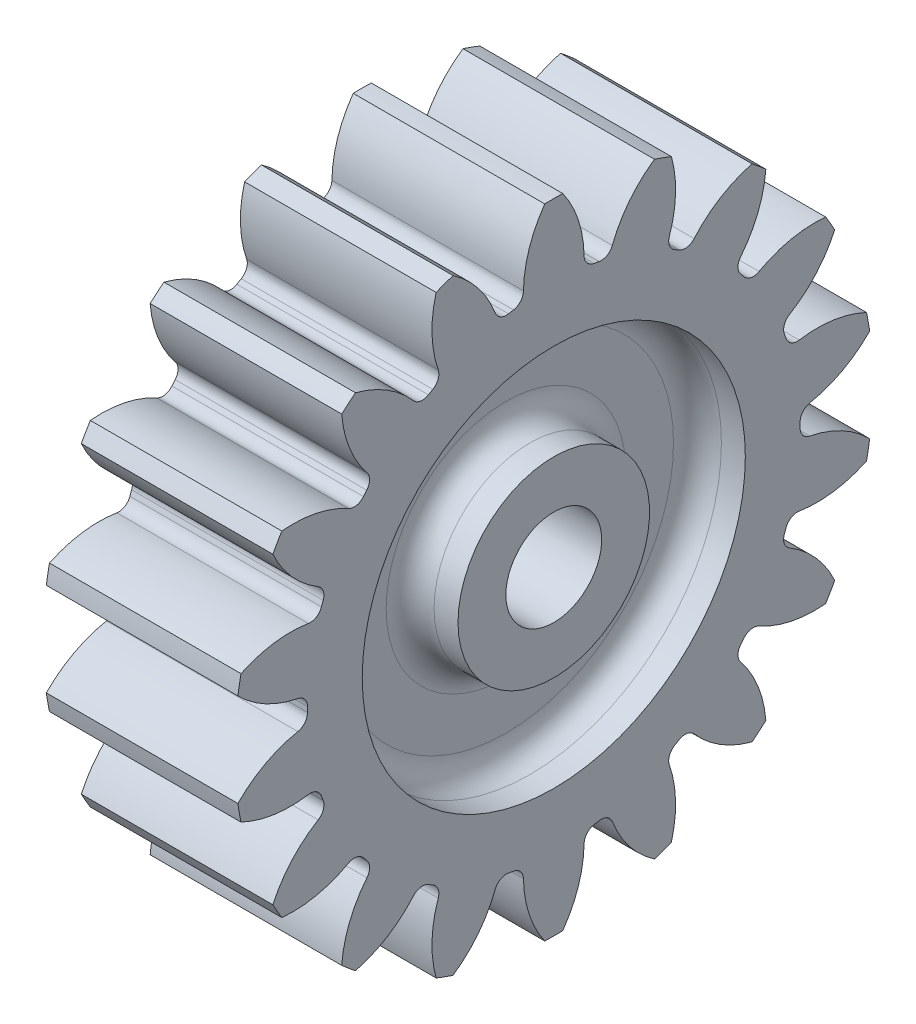
SolidWorks part; units mm, degrees
ref_plane "Front Plane" through (0, 0, 0) normal (0, 0, 1) x (1, 0, 0)
ref_plane "Top Plane" through (0, 0, 0) normal (0, 1, 0) x (1, 0, 0)
ref_plane "Right Plane" through (0, 0, 0) normal (1, 0, 0) x (0, 0, -1)
sketch "Sketch2" plane through (0, 0, 0) normal (0, 1, 0) x (1, 0, 0)
  line L0 (0, 2.4022) -> (0, -2.1136) construction
  line L1 (-2.9285, 0) -> (2.6948, 0) construction
  line L2 (-0.5, 0) -> (-0.5, 0.5)
  line L3 (-0.5, 1.667) -> (0.5, 1.667)
  line L4 (-0.5, 1) -> (-0.375, 1)
  line L5 (-0.25, 0.875) -> (-0.25, 0.625)
  line L6 (-0.375, 0.5) -> (-0.5, 0.5)
  line L7 (-0.5, 1) -> (-0.5, 1.667)
  line L8 (-0.5, 0.25) -> (0.5, 0.25)
  line L9 (0.5, 0) -> (0.5, 0.5)
  line L10 (0.375, 0.5) -> (0.5, 0.5)
  line L11 (0.25, 0.875) -> (0.25, 0.625)
  line L12 (0.5, 1) -> (0.375, 1)
  line L13 (0.5, 1) -> (0.5, 1.667)
  arc A0 (-0.25, 0.875) -> (-0.375, 1) centre (-0.375, 0.875) ccw
  arc A1 (-0.375, 0.5) -> (-0.25, 0.625) centre (-0.375, 0.625) ccw
  arc A2 (0.375, 0.5) -> (0.25, 0.625) centre (0.375, 0.625) cw
  arc A3 (0.25, 0.875) -> (0.375, 1) centre (0.375, 0.875) cw
  point P19 (0, 0.25)
  point P29 (0, 1.667)
  dimension "D6" = 0.125
  dimension "D7" = 0.125
  dimension "D1" = 1.667
  dimension "D2" = 0.5
  dimension "D3" = 0.5
  dimension "D4" = 1
  dimension "D5" = 0.25
  dimension "D8" = 0.25
revolve "Revolve1" add sketch "Sketch2" angle 360 about L1
sketch "Sketch3" plane through (0.5, 0, 0) normal (1, 0, 0) x (0, 0, -1)
  line L0 (0, 2.2686) -> (0, -2.043) construction
  line L1 (-2.6225, 0) -> (2.1229, 0) construction
  circle A0 centre (0, 0) radius 1.667
  circle A1 centre (0, 0) radius 1.286
  circle A2 centre (0, 0) radius 1.5
  arc A3 (-0.047, 1.6663) -> (-0.1584, 1.3287) centre (0.4415, 1.318) ccw
  arc A4 (0.047, 1.6663) -> (0.1585, 1.318) centre (-0.4415, 1.318) cw
  arc A5 (-0.2103, 1.2687) -> (-0.1584, 1.3287) centre (-0.2204, 1.3299) ccw
  arc A6 (0.2103, 1.2687) -> (0.1584, 1.3287) centre (0.2204, 1.3299) cw
  arc A7 (0.2363, 1.2641) -> (0.3056, 1.3028) centre (0.2477, 1.325) ccw
  arc A8 (0.5258, 1.5819) -> (0.3056, 1.3028) centre (0.8656, 1.0875) ccw
  arc A9 (0.6141, 1.5498) -> (0.5997, 1.1843) centre (0.0359, 1.3895) cw
  arc A10 (0.6315, 1.1203) -> (0.6033, 1.1944) centre (0.6619, 1.1743) cw
  arc A11 (0.6544, 1.107) -> (0.7328, 1.1197) centre (0.686, 1.1604) ccw
  arc A12 (1.0351, 1.3067) -> (0.7328, 1.1197) centre (1.1854, 0.7258) ccw
  arc A13 (1.1071, 1.2463) -> (0.9686, 0.9077) centre (0.509, 1.2934) cw
  arc A14 (0.9766, 0.8367) -> (0.9754, 0.9161) centre (1.0236, 0.8771) cw
  arc A15 (0.9936, 0.8164) -> (1.0715, 0.8016) centre (1.0415, 0.8558) ccw
  arc A16 (1.4196, 0.8739) -> (1.0715, 0.8016) centre (1.3621, 0.2766) ccw
  arc A17 (1.4666, 0.7925) -> (1.2206, 0.5217) centre (0.9206, 1.0413) cw
  arc A18 (1.2039, 0.4523) -> (1.2299, 0.5272) centre (1.2619, 0.4741) cw
  arc A19 (1.2129, 0.4274) -> (1.2811, 0.3867) centre (1.2714, 0.448) ccw
  arc A20 (1.6329, 0.3356) -> (1.2811, 0.3867) centre (1.3746, -0.2059) ccw
  arc A21 (1.6492, 0.2431) -> (1.3255, 0.0728) centre (1.2213, 0.6637) cw
  arc A22 (1.2859, 0.0132) -> (1.3361, 0.0747) centre (1.3479, 0.0139) cw
  arc A23 (1.2859, -0.0132) -> (1.3361, -0.0747) centre (1.3479, -0.0139) ccw
  arc A24 (1.6492, -0.2431) -> (1.3361, -0.0747) centre (1.2213, -0.6637) ccw
  arc A25 (1.6329, -0.3356) -> (1.2704, -0.385) centre (1.3746, 0.2059) cw
  arc A26 (1.2129, -0.4274) -> (1.2811, -0.3867) centre (1.2714, -0.448) cw
  arc A27 (1.2039, -0.4523) -> (1.2299, -0.5272) centre (1.2619, -0.4741) ccw
  arc A28 (1.4666, -0.7925) -> (1.2299, -0.5272) centre (0.9206, -1.0413) ccw
  arc A29 (1.4196, -0.8739) -> (1.0621, -0.7962) centre (1.3621, -0.2766) cw
  arc A30 (0.9936, -0.8164) -> (1.0715, -0.8016) centre (1.0415, -0.8558) cw
  arc A31 (0.9766, -0.8367) -> (0.9754, -0.9161) centre (1.0236, -0.8771) ccw
  arc A32 (1.1071, -1.2463) -> (0.9754, -0.9161) centre (0.509, -1.2934) ccw
  arc A33 (1.0351, -1.3067) -> (0.7257, -1.1115) centre (1.1854, -0.7258) cw
  arc A34 (0.6544, -1.107) -> (0.7328, -1.1197) centre (0.686, -1.1604) cw
  arc A35 (0.6315, -1.1203) -> (0.6033, -1.1944) centre (0.6619, -1.1743) ccw
  arc A36 (0.6141, -1.5498) -> (0.6033, -1.1944) centre (0.0359, -1.3895) ccw
  arc A37 (0.5258, -1.5819) -> (0.3018, -1.2927) centre (0.8656, -1.0875) cw
  arc A38 (0.2363, -1.2641) -> (0.3056, -1.3028) centre (0.2477, -1.325) cw
  arc A39 (0.2103, -1.2687) -> (0.1584, -1.3287) centre (0.2204, -1.3299) ccw
  arc A40 (0.047, -1.6663) -> (0.1584, -1.3287) centre (-0.4415, -1.318) ccw
  arc A41 (-0.047, -1.6663) -> (-0.1585, -1.318) centre (0.4415, -1.318) cw
  arc A42 (-0.2103, -1.2687) -> (-0.1584, -1.3287) centre (-0.2204, -1.3299) cw
  arc A43 (-0.2363, -1.2641) -> (-0.3056, -1.3028) centre (-0.2477, -1.325) ccw
  arc A44 (-0.5258, -1.5819) -> (-0.3056, -1.3028) centre (-0.8656, -1.0875) ccw
  arc A45 (-0.6141, -1.5498) -> (-0.5997, -1.1843) centre (-0.0359, -1.3895) cw
  arc A46 (-0.6315, -1.1203) -> (-0.6033, -1.1944) centre (-0.6619, -1.1743) cw
  arc A47 (-0.6544, -1.107) -> (-0.7328, -1.1197) centre (-0.686, -1.1604) ccw
  arc A48 (-1.0351, -1.3067) -> (-0.7328, -1.1197) centre (-1.1854, -0.7258) ccw
  arc A49 (-1.1071, -1.2463) -> (-0.9686, -0.9077) centre (-0.509, -1.2934) cw
  arc A50 (-0.9766, -0.8367) -> (-0.9754, -0.9161) centre (-1.0236, -0.8771) cw
  arc A51 (-0.9936, -0.8164) -> (-1.0715, -0.8016) centre (-1.0415, -0.8558) ccw
  arc A52 (-1.4196, -0.8739) -> (-1.0715, -0.8016) centre (-1.3621, -0.2766) ccw
  arc A53 (-1.4666, -0.7925) -> (-1.2206, -0.5217) centre (-0.9206, -1.0413) cw
  arc A54 (-1.2039, -0.4523) -> (-1.2299, -0.5272) centre (-1.2619, -0.4741) cw
  arc A55 (-1.2129, -0.4274) -> (-1.2811, -0.3867) centre (-1.2714, -0.448) ccw
  arc A56 (-1.6329, -0.3356) -> (-1.2811, -0.3867) centre (-1.3746, 0.2059) ccw
  arc A57 (-1.6492, -0.2431) -> (-1.3255, -0.0728) centre (-1.2213, -0.6637) cw
  arc A58 (-1.2859, -0.0132) -> (-1.3361, -0.0747) centre (-1.3479, -0.0139) cw
  arc A59 (-1.2859, 0.0132) -> (-1.3361, 0.0747) centre (-1.3479, 0.0139) ccw
  arc A60 (-1.6492, 0.2431) -> (-1.3361, 0.0747) centre (-1.2213, 0.6637) ccw
  arc A61 (-1.6329, 0.3356) -> (-1.2704, 0.385) centre (-1.3746, -0.2059) cw
  arc A62 (-1.2129, 0.4274) -> (-1.2811, 0.3867) centre (-1.2714, 0.448) cw
  arc A63 (-1.2039, 0.4523) -> (-1.2299, 0.5272) centre (-1.2619, 0.4741) ccw
  arc A64 (-1.4666, 0.7925) -> (-1.2299, 0.5272) centre (-0.9206, 1.0413) ccw
  arc A65 (-1.4196, 0.8739) -> (-1.0621, 0.7962) centre (-1.3621, 0.2766) cw
  arc A66 (-0.9936, 0.8164) -> (-1.0715, 0.8016) centre (-1.0415, 0.8558) cw
  arc A67 (-0.9766, 0.8367) -> (-0.9754, 0.9161) centre (-1.0236, 0.8771) ccw
  arc A68 (-1.1071, 1.2463) -> (-0.9754, 0.9161) centre (-0.509, 1.2934) ccw
  arc A69 (-1.0351, 1.3067) -> (-0.7257, 1.1115) centre (-1.1854, 0.7258) cw
  arc A70 (-0.6544, 1.107) -> (-0.7328, 1.1197) centre (-0.686, 1.1604) cw
  arc A71 (-0.6315, 1.1203) -> (-0.6033, 1.1944) centre (-0.6619, 1.1743) ccw
  arc A72 (-0.6141, 1.5498) -> (-0.6033, 1.1944) centre (-0.0359, 1.3895) ccw
  arc A73 (-0.5258, 1.5819) -> (-0.3018, 1.2927) centre (-0.8656, 1.0875) cw
  arc A74 (-0.2363, 1.2641) -> (-0.3056, 1.3028) centre (-0.2477, 1.325) cw
  point P209 (0, 0)
  circle M11 centre (0, 0) radius 1.667
  dimension "D1" = 3
  dimension "D2" = 0.381
  dimension "D3" = 0.214
  dimension "D6" = 1.2
  dimension "D5" = 0.124
  dimension "D4" = 18
  dimension "D7" = 0.047
extrude "Cut-Extrude1" cut sketch "Sketch3" against normal through all contours A73 A2 A3 M11 | A74 A1 A5 A3 A2 A73 | A72 A0 A69 A2 | A72 A2 A69 A70 A1 A71 | A68 A0 A65 A2 | A68 A2 A65 A66 A1 A67 | A64 A0 A61 A2 | A64 A2 A61 A62 A1 A63 | A60 A0 A57 A2 | A60 A2 A57 A58 A1 A59 | A56 A0 A53 A2 | A56 A2 A53 A54 A1 A55 | A52 A0 A49 A2 | A52 A2 A49 A50 A1 A51 | A48 A0 A45 A2 | A48 A2 A45 A46 A1 A47 | A44 A0 A41 A2 | A44 A2 A41 A42 A1 A43 | A40 A0 A37 A2 | A40 A2 A37 A38 A1 A39 | A36 A0 A33 A2 | A36 A2 A33 A34 A1 A35 | A32 A0 A29 A2 | A32 A2 A29 A30 A1 A31 | A28 A0 A25 A2 | A28 A2 A25 A26 A1 A27 | A24 A0 A21 A2 | A24 A2 A21 A22 A1 A23 | A20 A0 A17 A2 | A20 A2 A17 A18 A1 A19 | A16 A0 A13 A2 | A16 A2 A13 A14 A1 A15 | A12 A0 A9 A2 | A12 A2 A9 A10 A1 A11 | A8 A0 A4 A2 | A8 A2 A4 A6 A1 A7
